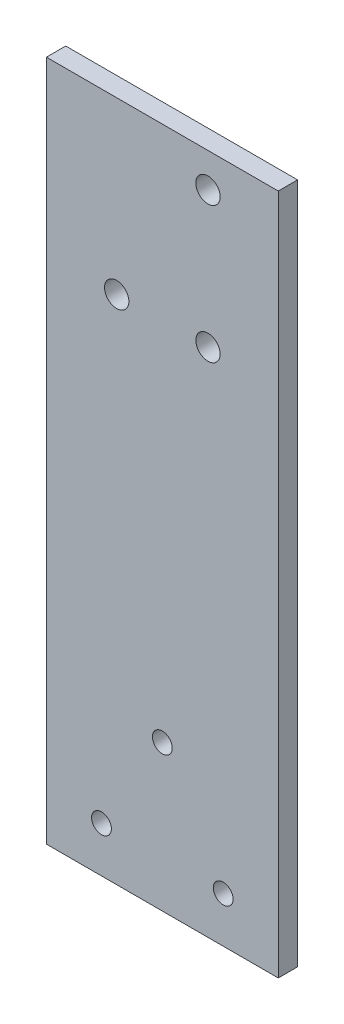
SolidWorks part; units mm, degrees
ref_plane "Front Plane" through (0, 0, 0) normal (0, 0, 1) x (1, 0, 0)
ref_plane "Top Plane" through (0, 0, 0) normal (0, 1, 0) x (1, 0, 0)
ref_plane "Right Plane" through (0, 0, 0) normal (1, 0, 0) x (0, 0, -1)
sketch "Sketch1" plane through (0, 0, 0) normal (0, 0, 1) x (1, 0, 0)
  line L0 (-40.8056, 168) -> (97.4829, 168) construction
  line L1 (0, 0) -> (76.2, 0)
  line L2 (0, 0) -> (0, 224)
  line L3 (0, 224) -> (76.2, 224)
  line L4 (76.2, 0) -> (76.2, 224)
  line L5 (38.1, 220.2353) -> (38.1, -14.183) construction
  line L7 (86.5141, 15) -> (-49.4392, 15) construction
  line L8 (53.1, 168) -> (53.1, 228.8793) construction
  circle A0 centre (23.1, 168) radius 4
  circle A1 centre (53.1, 168) radius 4
  circle A2 centre (58.1, 15) radius 3.25
  circle A3 centre (18.1, 15) radius 3.25
  circle A4 centre (53.1, 212.75) radius 4
  circle A5 centre (38.1, 48) radius 3.25
  dimension "D4" = 8
  dimension "D5" = 8
  dimension "D8" = 6.5
  dimension "D9" = 6.5
  dimension "D11" = 8
  dimension "D13" = 6.5
  dimension "D1" = 224
  dimension "D2" = 76.2
  dimension "D3" = 56
  dimension "D6" = 30
  dimension "D7" = 15
  dimension "D10" = 40
  dimension "D12" = 44.75
  dimension "D14" = 33
extrude "Boss-Extrude1" add sketch "Sketch1" along normal blind 6.35
equation "\"D9@Sketch1\"=\"D8@Sketch1\""
